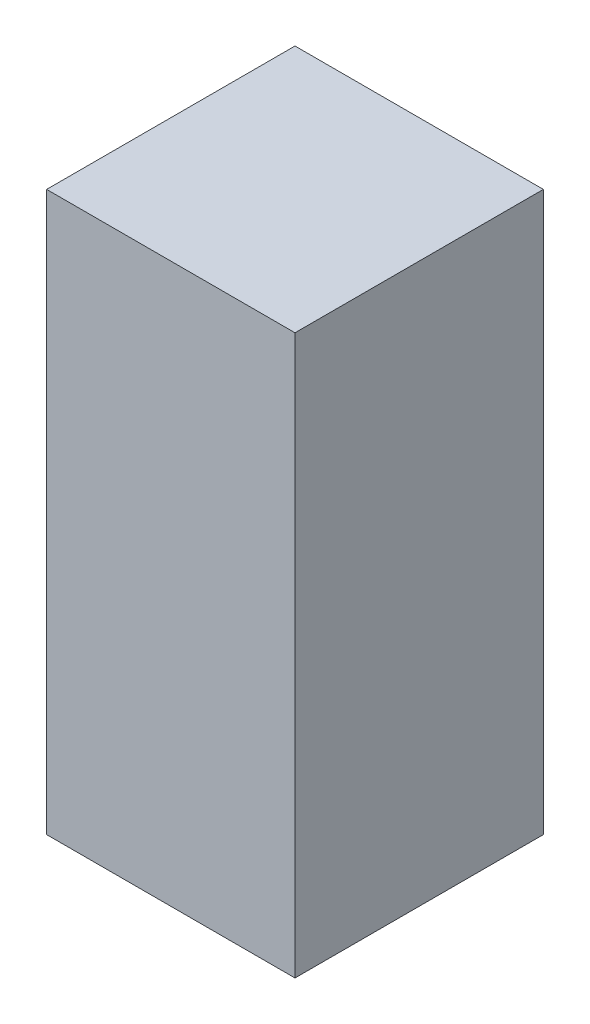
SolidWorks part; units mm, degrees
ref_plane "Front Plane" through (0, 0, 0) normal (0, 0, 1) x (1, 0, 0)
ref_plane "Top Plane" through (0, 0, 0) normal (0, 1, 0) x (1, 0, 0)
ref_plane "Right Plane" through (0, 0, 0) normal (1, 0, 0) x (0, 0, -1)
other "Configuration Table"
sketch "Sketch1" plane through (0, 0, 0) normal (0, 0, 1) x (1, 0, 0)
  line L1 (177.5, 552) -> (197.5, 552)
  line L2 (177.5, 552) -> (177.5, 597)
  line L3 (177.5, 597) -> (197.5, 597)
  line L4 (197.5, 552) -> (197.5, 597)
extrude "PACK_kose_plowu_1_1" add sketch "Sketch1" against normal blind 20 from offset 552.5 separate body
